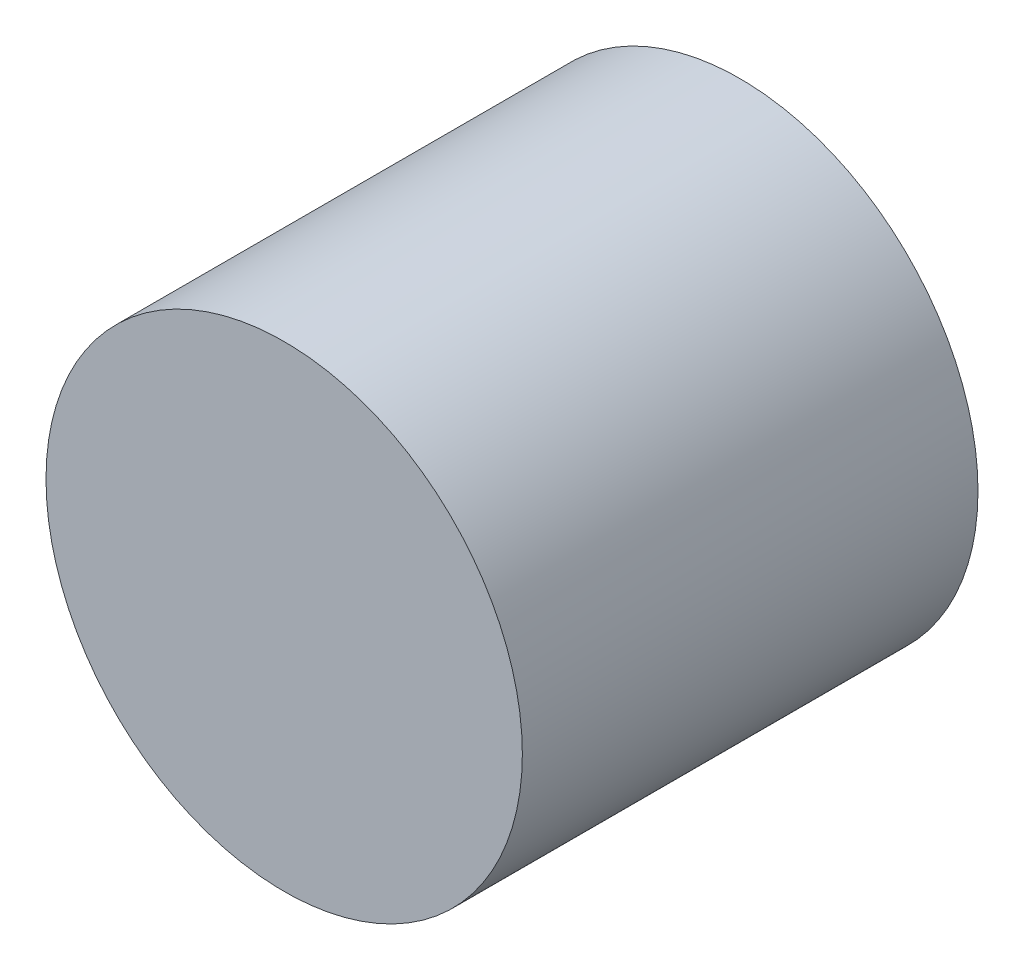
SolidWorks part; units mm, degrees
material "灵足rl05电机"
ref_plane "前视基准面" through (0, 0, 0) normal (0, 0, 1) x (1, 0, 0)
ref_plane "上视基准面" through (0, 0, 0) normal (0, 1, 0) x (1, 0, 0)
ref_plane "右视基准面" through (0, 0, 0) normal (1, 0, 0) x (0, 0, -1)
other "Configuration Table"
sketch "草图1" plane through (0, 0, 0) normal (0, 0, 1) x (1, 0, 0)
  circle A0 centre (0, 0) radius 23
  dimension "D1" = 46
extrude "凸台-拉伸1" add sketch "草图1" along normal blind 44
